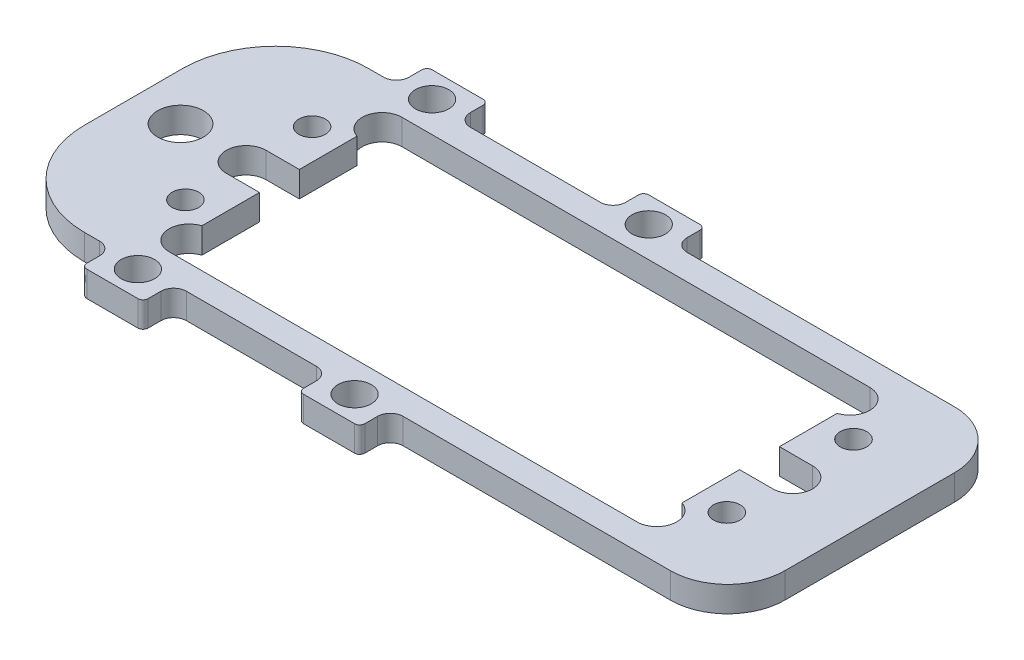
SolidWorks part; units mm, degrees
ref_plane "Alzado" through (0, 0, 0) normal (0, 0, 1) x (1, 0, 0)
ref_plane "Planta" through (0, 0, 0) normal (0, 1, 0) x (1, 0, 0)
ref_plane "Vista lateral" through (0, 0, 0) normal (1, 0, 0) x (0, 0, -1)
ref_plane "Plano1" through (0, 0, 0) normal (0, -1, 0) x (1, 0, 0)
sketch "Croquis1" plane through (0, 0, 0) normal (0, -1, 0) x (1, 0, 0)
  line L0 (-6.0223, -19.2405) -> (-6.0223, -20.828)
  line L1 (-5.3873, -21.463) -> (0.9627, -21.463)
  line L2 (1.5977, -20.828) -> (1.5977, -19.2405)
  line L3 (3.1852, -17.653) -> (36.4312, -17.653)
  line L4 (43.5348, -10.5494) -> (43.5348, 10.5494)
  line L5 (36.4312, 17.653) -> (3.1852, 17.653)
  line L6 (1.5977, 19.2405) -> (1.5977, 20.828)
  line L7 (0.9627, 21.463) -> (-5.3873, 21.463)
  line L8 (-6.0223, 20.828) -> (-6.0223, 19.2405)
  line L9 (-7.6098, 17.653) -> (-23.7556, 17.653)
  line L10 (-25.3431, 19.2405) -> (-25.3431, 20.828)
  line L11 (-25.9781, 21.463) -> (-32.3281, 21.463)
  line L12 (-32.9631, 20.828) -> (-32.9631, 19.2405)
  line L13 (-34.5506, 17.653) -> (-36.4312, 17.653)
  line L14 (-47.971, 6.1133) -> (-47.971, -6.1133)
  line L15 (-36.4312, -17.653) -> (-34.5506, -17.653)
  line L16 (-32.9631, -19.2405) -> (-32.9631, -20.828)
  line L17 (-32.3281, -21.463) -> (-25.9781, -21.463)
  line L18 (-25.3431, -20.828) -> (-25.3431, -19.2405)
  line L19 (-23.7556, -17.653) -> (-7.6098, -17.653)
  line L20 (-33.9725, 2.4765) -> (-29.845, 2.4765)
  line L21 (-29.845, 2.4765) -> (-29.845, 9.646)
  line L22 (-29.0805, 14.478) -> (29.0805, 14.478)
  line L23 (29.845, 9.646) -> (29.845, 2.4765)
  line L24 (29.845, 2.4765) -> (33.9725, 2.4765)
  line L25 (33.9725, -2.4765) -> (29.845, -2.4765)
  line L26 (29.845, -2.4765) -> (29.845, -9.646)
  line L27 (29.0805, -14.478) -> (-29.0805, -14.478)
  line L28 (-29.845, -9.646) -> (-29.845, -2.4765)
  line L29 (-29.845, -2.4765) -> (-33.9725, -2.4765)
  circle A0 centre (33.655, -7.874) radius 1.3525
  circle A1 centre (-33.655, 7.874) radius 1.3525
  circle A2 centre (-33.655, -7.874) radius 1.3525
  circle A3 centre (-2.2123, 18.288) radius 1.778
  circle A4 centre (-29.1531, -18.288) radius 1.778
  circle A5 centre (-2.2123, -18.288) radius 1.778
  arc A6 (-6.0223, -20.828) -> (-5.3873, -21.463) centre (-5.3873, -20.828) ccw
  arc A7 (0.9627, -21.463) -> (1.5977, -20.828) centre (0.9627, -20.828) ccw
  arc A8 (1.5977, -19.2405) -> (3.1852, -17.653) centre (3.1852, -19.2405) cw
  arc A9 (36.4312, -17.653) -> (43.5348, -10.5494) centre (36.4312, -10.5494) ccw
  arc A10 (43.5348, 10.5494) -> (36.4312, 17.653) centre (36.4312, 10.5494) ccw
  arc A11 (3.1852, 17.653) -> (1.5977, 19.2405) centre (3.1852, 19.2405) cw
  arc A12 (1.5977, 20.828) -> (0.9627, 21.463) centre (0.9627, 20.828) ccw
  arc A13 (-5.3873, 21.463) -> (-6.0223, 20.828) centre (-5.3873, 20.828) ccw
  arc A14 (-6.0223, 19.2405) -> (-7.6098, 17.653) centre (-7.6098, 19.2405) cw
  arc A15 (-23.7556, 17.653) -> (-25.3431, 19.2405) centre (-23.7556, 19.2405) cw
  arc A16 (-25.3431, 20.828) -> (-25.9781, 21.463) centre (-25.9781, 20.828) ccw
  arc A17 (-32.3281, 21.463) -> (-32.9631, 20.828) centre (-32.3281, 20.828) ccw
  arc A18 (-32.9631, 19.2405) -> (-34.5506, 17.653) centre (-34.5506, 19.2405) cw
  arc A19 (-36.4312, 17.653) -> (-47.971, 6.1133) centre (-36.4312, 6.1133) ccw
  arc A20 (-47.971, -6.1133) -> (-36.4312, -17.653) centre (-36.4312, -6.1133) ccw
  arc A21 (-34.5506, -17.653) -> (-32.9631, -19.2405) centre (-34.5506, -19.2405) cw
  arc A22 (-32.9631, -20.828) -> (-32.3281, -21.463) centre (-32.3281, -20.828) ccw
  arc A23 (-25.9781, -21.463) -> (-25.3431, -20.828) centre (-25.9781, -20.828) ccw
  arc A24 (-25.3431, -19.2405) -> (-23.7556, -17.653) centre (-23.7556, -19.2405) cw
  arc A25 (-7.6098, -17.653) -> (-6.0223, -19.2405) centre (-7.6098, -19.2405) cw
  circle A26 centre (-29.1531, 18.288) radius 1.778
  circle A27 centre (33.655, 7.874) radius 1.3525
  arc A28 (-29.845, 9.646) -> (-29.0805, 14.478) centre (-29.0805, 12.0015) cw
  arc A29 (29.0805, 14.478) -> (29.845, 9.646) centre (29.0805, 12.0015) cw
  arc A30 (33.9725, 2.4765) -> (33.9725, -2.4765) centre (33.9725, 0) cw
  arc A31 (29.845, -9.646) -> (29.0805, -14.478) centre (29.0805, -12.0015) cw
  arc A32 (-29.0805, -14.478) -> (-29.845, -9.646) centre (-29.0805, -12.0015) cw
  arc A33 (-33.9725, -2.4765) -> (-33.9725, 2.4765) centre (-33.9725, 0) cw
extrude "Saliente-Extruir1" add sketch "Croquis1" against normal blind 3.175
sketch "Croquis5" plane through (0, 3.175, 0) normal (0, 1, 0) x (1, 0, 0)
  line L0 (-39.5889, 0) -> (-42.1389, 0) construction
  line L1 (-36.449, 0) -> (-39.5889, 0) construction
  line L2 (-44.6889, 0) -> (-47.971, 0) construction
  line L3 (-47.971, -6.1133) -> (-47.971, 6.1133) construction
  arc A0 (-33.9725, 2.4765) -> (-33.9725, -2.4765) centre (-33.9725, 0) ccw construction
  circle A1 centre (-42.1389, 0) radius 2.55
extrude "Cortar-Extruir1" cut sketch "Croquis5" against normal through all
sketch "Croquis6" plane through (0, 3.175, 0) normal (0, 1, 0) x (1, 0, 0)
  circle A0 centre (-29.1531, 18.288) radius 2.078
  circle A1 centre (-33.655, 7.874) radius 1.6526
  circle A2 centre (-33.655, -7.874) radius 1.6526
  circle A3 centre (-29.1531, -18.288) radius 2.078
  circle A4 centre (-2.2123, -18.288) radius 2.078
  circle A5 centre (-42.1389, 0) radius 2.85
  circle A6 centre (-2.2123, 18.288) radius 2.078
  circle A7 centre (33.655, 7.874) radius 1.6526
  circle A8 centre (33.655, -7.874) radius 1.6526
  dimension "D1" = 4.156
  dimension "D2" = 3.3051
  dimension "D3" = 5.7
  dimension "D4" = 3.3051
  dimension "D5" = 4.156
  dimension "D6" = 4.156
  dimension "D7" = 4.156
  dimension "D8" = 3.3051
  dimension "D9" = 3.3051
extrude "Cortar-Extruir2" cut sketch "Croquis6" against normal through all
